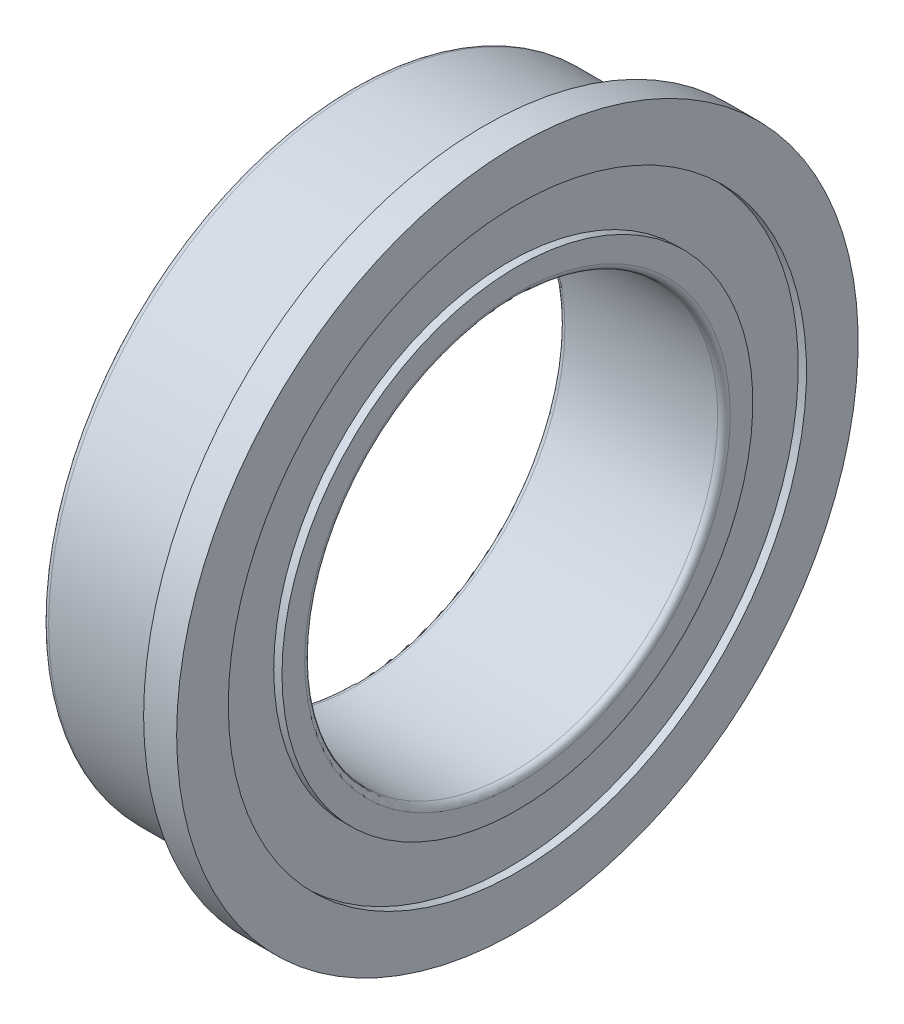
SolidWorks part; units mm, degrees
material "SUJ2"
ref_plane "Front Plane" through (0, 0, 0) normal (0, 0, 1) x (1, 0, 0)
ref_plane "Top Plane" through (0, 0, 0) normal (0, 1, 0) x (1, 0, 0)
ref_plane "Right Plane" through (0, 0, 0) normal (1, 0, 0) x (0, 0, -1)
sketch "Sketch1" plane through (0, 0, 0) normal (0, 0, 1) x (1, 0, 0)
  line L0 (-3.2, 0) -> (0.8, 0) construction
  line L1 (0, 7.7) -> (0, 8.25)
  line L2 (0, 8.25) -> (0.8, 8.25)
  line L3 (0.8, 8.25) -> (0.8, 7)
  line L4 (0.8, 5) -> (-3.2, 5)
  line L5 (-3.2, 5) -> (-3.2, 5.7)
  line L6 (-3.2, 7.5) -> (-0.2, 7.5)
  line L7 (-3.2, 7) -> (-3, 7)
  line L8 (-3, 7) -> (-3, 5.7)
  line L9 (-3, 5.7) -> (-3.2, 5.7)
  line L10 (0.8, 7) -> (0.6, 7)
  line L11 (0.6, 7) -> (0.6, 5.7)
  line L12 (0.6, 5.7) -> (0.8, 5.7)
  line L13 (-3.2, 7) -> (-3.2, 7.5)
  line L14 (0.8, 5.7) -> (0.8, 5)
  arc A0 (-0.2, 7.5) -> (0, 7.7) centre (0, 7.5) ccw
  dimension "FIX_1" = 0.2
  dimension "D_s" = 10
  dimension "C" = 0.8
  dimension "MSM_2" = 11.4
  dimension "MSM_1" = 14
  dimension "D" = 15
  dimension "D1." = 16.5
  dimension "B" = 4
  dimension "MSM_3" = 0.2
revolve "Revolve1" add sketch "Sketch1" angle 360 about L0
fillet "Fillet1" radius 0.15 3 edges at (0.8, 0, 5) (-3.2, 0, 5) (-3.2, 0, 7.5)
